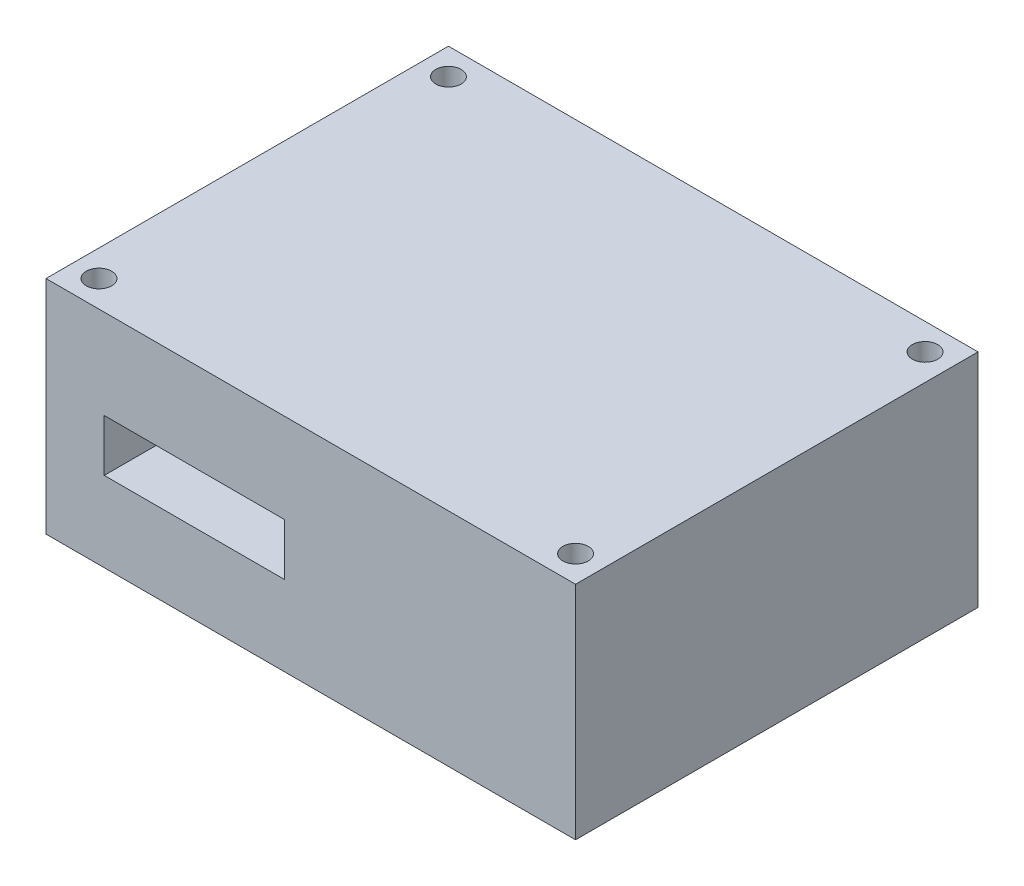
SolidWorks part; units mm, degrees
ref_plane "Front Plane" through (0, 0, 0) normal (0, 0, 1) x (1, 0, 0)
ref_plane "Top Plane" through (0, 0, 0) normal (0, 1, 0) x (1, 0, 0)
ref_plane "Right Plane" through (0, 0, 0) normal (1, 0, 0) x (0, 0, -1)
sketch "Sketch1" plane through (0, 0, 0) normal (0, 1, 0) x (1, 0, 0)
  line L1 (-26.2584, 16.118) -> (23.7416, 16.118)
  line L2 (-26.2584, 16.118) -> (-26.2584, -21.882)
  line L3 (-26.2584, -21.882) -> (23.7416, -21.882)
  line L4 (23.7416, 16.118) -> (23.7416, -21.882)
  dimension "D1" = 38
  dimension "D2" = 50
extrude "Boss-Extrude1" add sketch "Sketch1" along normal blind 20.9
sketch "Sketch2" plane through (0, 20.9, 0) normal (0, 1, 0) x (1, 0, 0)
  line L0 (23.7416, 16.118) -> (-26.2584, 16.118) construction
  line L4 (-26.2584, 16.118) -> (-26.2584, -21.882) construction
  point P0 (-23.7584, 13.618)
  point P1 (21.2416, 13.618)
  point P2 (21.2416, -19.382)
  point P3 (-23.7584, -19.382)
  dimension "D1" = 2.5
  dimension "D2" = 33
  dimension "D3" = 33
  dimension "D4" = 2.5
  dimension "D5" = 45
  dimension "D6" = 45
  dimension "D7" = 2.5
  dimension "D8" = 2.5
hole_wizard "M2 Clearance Hole1" positions "Sketch3" profile "Sketch4" hole size "M2" standard "ISO"
sketch "Sketch3" plane through (0, 20.9, 0) normal (0, 1, 0) x (1, 0, 0)
  point P0 (-23.7584, 13.618)
  point P3 (-23.7584, -19.382)
  point P6 (21.2416, -19.382)
  point P9 (21.2416, 13.618)
sketch "Sketch4" plane through (-23.7584, 20.9, -13.618) normal (1, 0, 0) x (0, 0, 1)
  line L0 (0, 0) -> (0, 10.721)
  line L1 (0, 10.721) -> (1.2, 10)
  line L2 (1.2, 10) -> (1.2, 0)
  line L5 (1.2, 0) -> (0, 0)
  line L10 (0, 10.721) -> (-1.2, 10) construction
  line L11 (0, -6.35) -> (0, 107.95) construction
  dimension "Hole Dia." = 2.4
  dimension "Hole Depth" = 10
  dimension "Drill Angle" = 118
sketch "Sketch5" plane through (0, 0, -16.118) normal (0, 0, -1) x (-1, 0, 0)
  line L0 (26.2584, 2.45) -> (-23.7416, 2.45) construction
  line L1 (26.2584, 20.9) -> (26.2584, 0) construction
  line L2 (-23.7416, 20.9) -> (-23.7416, 0) construction
  line L3 (-23.7416, 0) -> (26.2584, 0) construction
  circle A0 centre (-9.5416, 10.45) radius 9
  circle A1 centre (20.2584, 2.45) radius 1.25
  circle A2 centre (16.2584, 2.45) radius 1.25
  circle A3 centre (12.2584, 2.45) radius 1.25
  circle A4 centre (8.2584, 2.45) radius 1.25
  circle A5 centre (-9.5416, 10.45) radius 6
  dimension "D4" = 2.5
  dimension "D5" = 2.5
  dimension "D6" = 2.5
  dimension "D7" = 2.5
  dimension "D12" = 18
  dimension "D13" = 12
  dimension "D1" = 2.45
  dimension "D2" = 10.45
  dimension "D3" = 35.8
  dimension "D8" = 6
  dimension "D9" = 4
  dimension "D10" = 4
  dimension "D11" = 4
extrude "Cut-Extrude1" cut sketch "Sketch5" against normal blind 5
sketch "Sketch6" plane through (0, 0, 21.882) normal (0, 0, 1) x (1, 0, 0)
  line L0 (23.7416, 10) -> (-26.2584, 10) construction
  line L2 (-26.2584, 20.9) -> (-26.2584, 0) construction
  line L4 (-3.7584, 7.55) -> (-20.7584, 7.55)
  line L5 (-3.7584, 7.55) -> (-3.7584, 12.45)
  line L6 (-3.7584, 12.45) -> (-20.7584, 12.45)
  line L7 (-20.7584, 7.55) -> (-20.7584, 12.45)
  line L8 (-3.7584, 7.55) -> (-20.7584, 12.45) construction
  line L9 (-3.7584, 12.45) -> (-20.7584, 7.55) construction
  line L10 (-26.2584, 0) -> (23.7416, 0) construction
  point P6 (-12.2584, 10)
  dimension "D1" = 17
  dimension "D2" = 4.9
  dimension "D3" = 5.5
  dimension "D4" = 7.55
extrude "Cut-Extrude2" cut sketch "Sketch6" against normal blind 5
